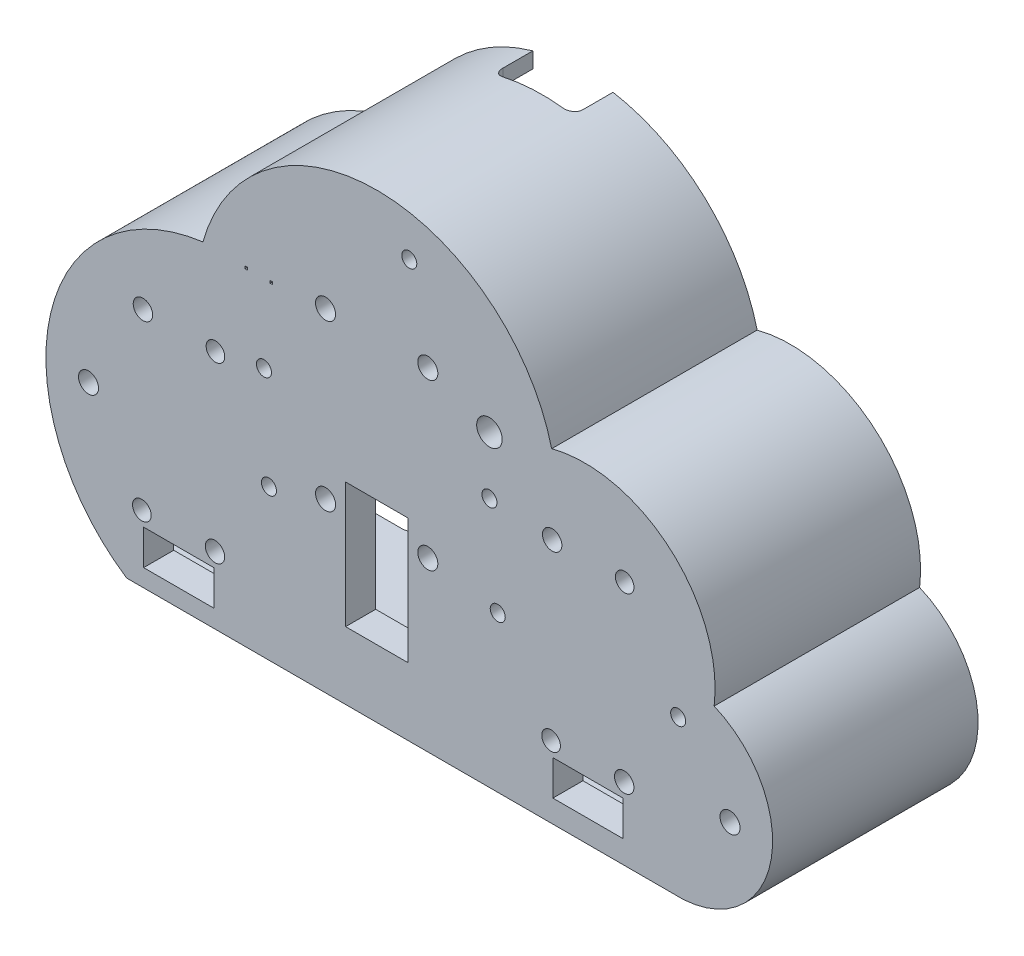
SolidWorks part; units mm, degrees
ref_plane "Plan de face" through (0, 0, 0) normal (0, 0, 1) x (1, 0, 0)
ref_plane "Plan de dessus" through (0, 0, 0) normal (0, 1, 0) x (1, 0, 0)
ref_plane "Plan de droite" through (0, 0, 0) normal (1, 0, 0) x (0, 0, -1)
sketch "Esquisse2" plane through (0, 0, 0) normal (0, 0, 1) x (1, 0, 0)
  line L5 (-48.6089, -52.6472) -> (61.4744, -52.6472)
  arc A0 (64.3021, -21.1783) -> (33.0075, 5.1842) centre (41.8849, -16.0335) ccw construction
  arc A1 (33.0075, 5.1842) -> (-31.9025, 7.2761) centre (0.3631, 0.3528) ccw construction
  arc A2 (-31.9025, 7.2761) -> (-48.6089, -52.6472) centre (-29.6369, -25.646) ccw construction
  arc A3 (61.4744, -52.6472) -> (64.3021, -21.1783) centre (60.3631, -36.6858) ccw construction
  arc A4 (64.3021, -21.1783) -> (33.0075, 5.1842) centre (41.8849, -16.0335) ccw
  arc A5 (33.0075, 5.1842) -> (-31.9025, 7.2761) centre (0.3631, 0.3528) ccw
  arc A6 (-31.9025, 7.2761) -> (-48.6089, -52.6472) centre (-29.6369, -25.646) ccw
  arc A7 (61.4744, -52.6472) -> (64.3021, -21.1783) centre (60.3631, -36.6858) ccw
extrude "Boss.-Extru.1" add sketch "Esquisse2" along normal blind 6
sketch "Esquisse3" plane through (0, 0, 0) normal (0, 0, 1) x (1, 0, 0)
  line L2 (-49.5349, -55.6472) -> (61.5742, -55.6472)
  line L3 (-49.5349, -55.6472) -> (61.5742, -55.6472)
  line L4 (-48.6089, -52.6472) -> (61.4744, -52.6472)
  line L5 (-48.6089, -52.6472) -> (61.4744, -52.6472)
  arc A8 (61.5742, -55.6472) -> (67.6965, -19.1581) centre (60.3631, -36.6858) ccw
  arc A9 (-34.3063, 10.0499) -> (-49.5349, -55.6472) centre (-29.6369, -25.646) ccw
  arc A10 (35.2808, 9.1138) -> (-34.3063, 10.0499) centre (0.3631, 0.3528) ccw
  arc A11 (67.6965, -19.1581) -> (35.2808, 9.1138) centre (41.8849, -16.0335) ccw
  arc A12 (61.5742, -55.6472) -> (67.6965, -19.1581) centre (60.3631, -36.6858) ccw
  arc A13 (-34.3063, 10.0499) -> (-49.5349, -55.6472) centre (-29.6369, -25.646) ccw
  arc A14 (35.2808, 9.1138) -> (-34.3063, 10.0499) centre (0.3631, 0.3528) ccw
  arc A15 (67.6965, -19.1581) -> (35.2808, 9.1138) centre (41.8849, -16.0335) ccw
  arc A16 (61.4744, -52.6472) -> (64.3021, -21.1783) centre (60.3631, -36.6858) ccw
  arc A17 (64.3021, -21.1783) -> (33.0075, 5.1842) centre (41.8849, -16.0335) ccw
  arc A18 (33.0075, 5.1842) -> (-31.9025, 7.2761) centre (0.3631, 0.3528) ccw
  arc A19 (-31.9025, 7.2761) -> (-48.6089, -52.6472) centre (-29.6369, -25.646) ccw
  arc A20 (61.4744, -52.6472) -> (64.3021, -21.1783) centre (60.3631, -36.6858) ccw
  arc A21 (64.3021, -21.1783) -> (33.0075, 5.1842) centre (41.8849, -16.0335) ccw
  arc A22 (33.0075, 5.1842) -> (-31.9025, 7.2761) centre (0.3631, 0.3528) ccw
  arc A23 (-31.9025, 7.2761) -> (-48.6089, -52.6472) centre (-29.6369, -25.646) ccw
  dimension "D1" = 3
  dimension "D2" = 0
extrude "Boss.-Extru.2" add sketch "Esquisse3" against normal blind 35 and the other way up to surface (6 mm away) other way up to face at (15.8872, -14.5312, 6)
sketch "Esquisse5" plane through (0, -55.6472, 0) normal (0, -1, 0) x (1, 0, 0)
  line L5 (-49.5349, 6) -> (61.5742, 6) construction
  line L10 (-1.4803, -15) -> (13.5197, -15)
  line L11 (-1.4803, -15) -> (-1.4803, -35)
  line L12 (-1.4803, -35) -> (13.5197, -35)
  line L13 (13.5197, -15) -> (13.5197, -35)
  line L14 (-1.4803, -15) -> (13.5197, -35) construction
  line L15 (-1.4803, -35) -> (13.5197, -15) construction
  line L16 (-49.5349, -35) -> (61.5742, -35) construction
  point P0 (6.0197, -25)
  point P9 (6.0197, 6)
  point P12 (6.0197, -35)
  dimension "D1" = 15
  dimension "D2" = 20
extrude "Enlèv. mat.-Extru.2" cut sketch "Esquisse5" against normal up to next
fillet "Congé1" radius 5 2 edges at (13.5197, -54.1472, -15) (-1.4803, -54.1472, -15)
sketch "Esquisse6" plane through (0, -55.6472, 0) normal (0, -1, 0) x (1, 0, 0)
  line L0 (0.5525, -35) -> (0.5525, 33.4432) construction
  line L1 (-41.4803, -27) -> (-25.4803, -27)
  line L2 (-41.4803, -27) -> (-41.4803, -35)
  line L4 (-25.4803, -27) -> (-25.4803, -35)
  line L5 (40.5197, -35) -> (40.5197, -27)
  line L6 (13.5197, -35) -> (61.5742, -35) construction
  line L7 (-31.9025, -35) -> (33.0075, -35) construction
  line L8 (-1.4803, -20) -> (-1.4803, -35) construction
  line L9 (-49.5349, -35) -> (-1.4803, -35) construction
  line L10 (-41.4803, -35) -> (-25.4803, -35)
  line L11 (40.5197, -27) -> (56.5197, -27)
  line L12 (56.5197, -27) -> (56.5197, -35)
  line L13 (13.5197, -35) -> (13.5197, -20) construction
  line L14 (40.5197, -35) -> (56.5197, -35)
  point P0 (-34.6274, -42.1137)
  dimension "D1" = 24
  dimension "D2" = 8
  dimension "D3" = 16
  dimension "D4" = 27
extrude "Enlèv. mat.-Extru.3" cut sketch "Esquisse6" against normal up to next
sketch "Esquisse7" plane through (0, 0, 0) normal (0, 1, 0) x (1, 0, 0)
  line L5 (-9.4803, 35) -> (-9.4803, 27)
  line L6 (-9.4803, 27) -> (6.5197, 27)
  line L7 (6.5197, 27) -> (6.5197, 35)
  line L8 (35.2808, 35) -> (-34.3063, 35) construction
  line L9 (6.5197, 35) -> (-9.4803, 35)
  line L10 (13.5197, 35) -> (13.5197, 20) construction
  point P8 (13.5197, 27.5)
  dimension "D1" = 7
  dimension "D2" = 16
  dimension "D3" = 8
extrude "Enlèv. mat.-Extru.4" cut sketch "Esquisse7" along normal up to next
fillet "Congé2" radius 2 6 edges at (-25.4803, -54.1472, -27) (-41.4803, -54.1472, -27) (56.5197, -54.1472, -27) (40.5197, -54.1472, -27) (6.5197, 34.298, -27) (-9.4803, 33.4157, -27)
sketch "Esquisse8" plane through (0, -55.6472, 0) normal (0, -1, 0) x (-1, 0, 0)
  line L3 (-8.5197, 15) -> (-3.5197, 15) construction
  text T0 "<b>POWER</b>" font "Century Gothic" height in points 18
  point P3 (-6.0197, 15)
  dimension "D1" = 10
  dimension "D2" = 15
extrude "Enlèv. mat.-Extru.5" [suppressed] cut sketch "Esquisse8" against normal up to next
sketch "Esquisse10" plane through (0, 0, 0) normal (0, 0, 1) x (1, 0, 0)
  line L0 (0, -77.7233) -> (0, 74.8323) construction
  line L2 (-5.8369, -17.1972) -> (-5.8369, -28.1972) construction
  line L3 (6.5631, -28.1972) -> (6.5631, -17.1972) construction
  line L4 (6.5631, -17.1972) -> (-5.8369, -17.1972) construction
  line L5 (-5.8369, -17.1972) -> (-5.8369, -42.1972)
  line L6 (6.5631, -42.1972) -> (6.5631, -17.1972)
  line L7 (6.5631, -17.1972) -> (-5.8369, -17.1972)
  line L8 (6.5631, -42.1972) -> (-5.8369, -42.1972)
  line L9 (-49.5349, -55.6472) -> (61.5742, -55.6472) construction
  line L10 (-32.1353, -45.1472) -> (-32.1353, -49.6472) construction
  line L11 (-46.1353, -49.6472) -> (-46.1353, -45.1472) construction
  line L12 (-46.1353, -49.6472) -> (-46.1353, -45.1472)
  line L13 (-32.1353, -45.1472) -> (-32.1353, -49.6472)
  line L14 (35.5197, -48.6472) -> (35.5197, -44.1472) construction
  line L15 (35.5197, -48.6472) -> (35.5197, -44.1472)
  line L16 (49.5197, -44.1472) -> (49.5197, -48.6472) construction
  line L17 (49.5197, -44.1472) -> (49.5197, -48.6472)
  line L18 (35.5197, -44.1472) -> (49.5197, -44.1472)
  line L19 (49.5197, -48.6472) -> (49.5197, -51.1472)
  line L20 (49.5197, -51.1472) -> (35.5197, -51.1472)
  line L21 (35.5197, -51.1472) -> (35.5197, -48.6472)
  line L22 (-46.1353, -45.1472) -> (-32.1353, -45.1472)
  line L23 (-32.1353, -49.6472) -> (-32.1353, -52.1472)
  line L24 (-32.1353, -52.1472) -> (-46.1353, -52.1472)
  line L25 (-46.1353, -52.1472) -> (-46.1353, -49.6472)
  line L26 (-20.3869, 9.6028) -> (-20.8869, 9.6028) construction
  line L27 (-20.8869, 9.6028) -> (-20.8869, 10.1028) construction
  line L28 (-20.8869, 10.1028) -> (-20.3869, 10.1028) construction
  line L29 (-20.3869, 10.1028) -> (-20.3869, 9.6028) construction
  line L30 (-25.8869, 10.1028) -> (-25.3869, 10.1028) construction
  line L31 (-25.3869, 10.1028) -> (-25.3869, 9.6028) construction
  line L32 (-25.3869, 9.6028) -> (-25.8869, 9.6028) construction
  line L33 (-25.8869, 9.6028) -> (-25.8869, 10.1028) construction
  line L34 (-20.3869, 9.6028) -> (-20.8869, 9.6028)
  line L35 (-20.8869, 9.6028) -> (-20.8869, 10.1028)
  line L36 (-20.8869, 10.1028) -> (-20.3869, 10.1028)
  line L37 (-20.3869, 10.1028) -> (-20.3869, 9.6028)
  line L38 (-25.8869, 10.1028) -> (-25.3869, 10.1028)
  line L39 (-25.3869, 10.1028) -> (-25.3869, 9.6028)
  line L40 (-25.3869, 9.6028) -> (-25.8869, 9.6028)
  line L41 (-25.8869, 9.6028) -> (-25.8869, 10.1028)
  circle A0 centre (-57.1353, -25.6472) radius 2
  circle A3 centre (60.5197, -24.6472) radius 1.5 construction
  circle A4 centre (10.5631, -22.1472) radius 2 construction
  circle A5 centre (10.5631, 10.7528) radius 2 construction
  circle A6 centre (-9.8369, 10.7528) radius 2 construction
  circle A7 centre (10.5631, -22.1472) radius 2
  circle A8 centre (10.5631, 10.7528) radius 2
  circle A9 centre (-9.8369, 10.7528) radius 2
  circle A10 centre (-22.1369, -5.6972) radius 1.5 construction
  circle A11 centre (-22.1369, -5.6972) radius 1.5
  circle A12 centre (22.8631, -5.6972) radius 1.5 construction
  circle A13 centre (22.8631, -5.6972) radius 1.5
  circle A14 centre (-9.8369, -22.1472) radius 2 construction
  circle A15 centre (-9.8369, -22.1472) radius 2
  circle A16 centre (70.8647, -37.6472) radius 2
  circle A17 centre (6.8647, 27.5875) radius 1.5 construction
  circle A18 centre (6.8647, 27.5875) radius 1.5
  circle A19 centre (-46.4898, -42.3837) radius 1.8635 construction
  circle A20 centre (-31.8981, -42.2409) radius 1.9343 construction
  circle A21 centre (-46.2782, -7.5912) radius 1.9397 construction
  circle A22 centre (-31.8106, -7.6386) radius 1.8546 construction
  circle A23 centre (-21.1353, -25.6472) radius 1.5 construction
  circle A24 centre (-46.4898, -42.3837) radius 1.8635
  circle A25 centre (-31.8981, -42.2409) radius 1.9343
  circle A26 centre (-46.2782, -7.5912) radius 1.9397
  circle A27 centre (-31.8106, -7.6386) radius 1.8546
  circle A28 centre (-21.1353, -25.6472) radius 1.5
  circle A29 centre (24.5197, -24.6472) radius 1.5 construction
  circle A30 centre (60.5197, -24.6472) radius 1.5
  circle A31 centre (24.5197, -24.6472) radius 1.5
  circle A32 centre (35.3768, -6.5912) radius 1.9397 construction
  circle A33 centre (49.8444, -6.6386) radius 1.8546 construction
  circle A34 centre (49.7569, -41.2409) radius 1.9343 construction
  circle A35 centre (35.1653, -41.3837) radius 1.8635 construction
  circle A36 centre (35.3768, -6.5912) radius 1.9397
  circle A37 centre (49.8444, -6.6386) radius 1.8546
  circle A38 centre (49.7569, -41.2409) radius 1.9343
  circle A39 centre (35.1653, -41.3837) radius 1.8635
  circle A40 centre (22.8631, 5.7528) radius 2.55
  point P88 (0, 0)
  dimension "D1" = 30
  dimension "D2" = 4
  dimension "D5" = 18
  dimension "D6" = 64
  dimension "D9" = 5.1
  dimension "D3" = 64
  dimension "D4" = 25
  dimension "D7" = 7
  dimension "D8" = 7
  dimension "D10" = 5
extrude "Enlèv. mat.-Extru.6" cut sketch "Esquisse10" along normal through all
